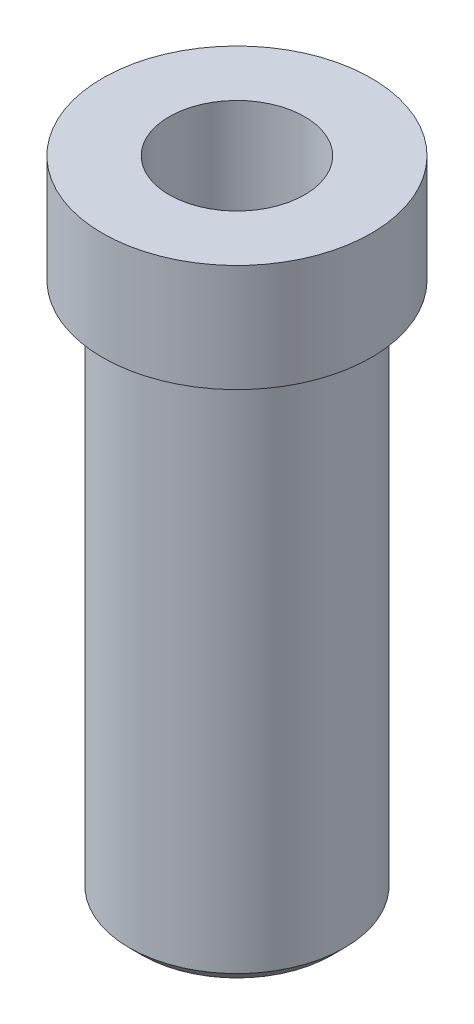
SolidWorks part; units mm, degrees
ref_plane "Front Plane" through (0, 0, 0) normal (0, 0, 1) x (1, 0, 0)
ref_plane "Top Plane" through (0, 0, 0) normal (0, 1, 0) x (1, 0, 0)
ref_plane "Right Plane" through (0, 0, 0) normal (1, 0, 0) x (0, 0, -1)
sketch "Sketch1" plane through (0, 0, 0) normal (0, 1, 0) x (1, 0, 0)
  circle A0 centre (0, 0) radius 0.5
  dimension "D1" = 1
extrude "Boss-Extrude1" add sketch "Sketch1" along normal blind 2.5
sketch "Sketch2" plane through (0, 2.5, 0) normal (0, 1, 0) x (1, 0, 0)
  circle A0 centre (0, 0) radius 0.625
  dimension "D1" = 1.25
extrude "Boss-Extrude2" add sketch "Sketch2" along normal blind 0.5
hole_wizard "Ø12.0mm Dowel Hole1" positions "Sketch3" profile "Sketch4" hole size "Ø12.0" standard "ISO" end condition through all
sketch "Sketch3" plane through (0, 3, 0) normal (0, 1, 0) x (1, 0, 0)
  point P0 (0, 0)
sketch "Sketch4" plane through (0, 3, 0) normal (1, 0, 0) x (0, 0, 1)
  line L0 (0, 0) -> (0, 3)
  line L1 (0, 3) -> (0.315, 3)
  line L2 (0.315, 3) -> (0.315, 0)
  line L5 (0.315, 0) -> (0, 0)
  line L11 (0, -6.35) -> (0, 107.95) construction
  dimension "Thru Hole Dia." = 0.63
  dimension "Thru Hole Depth" = 3
chamfer "Chamfer1" distance 0.06 angle 45 1 edges at (0, 0, 0.5)
